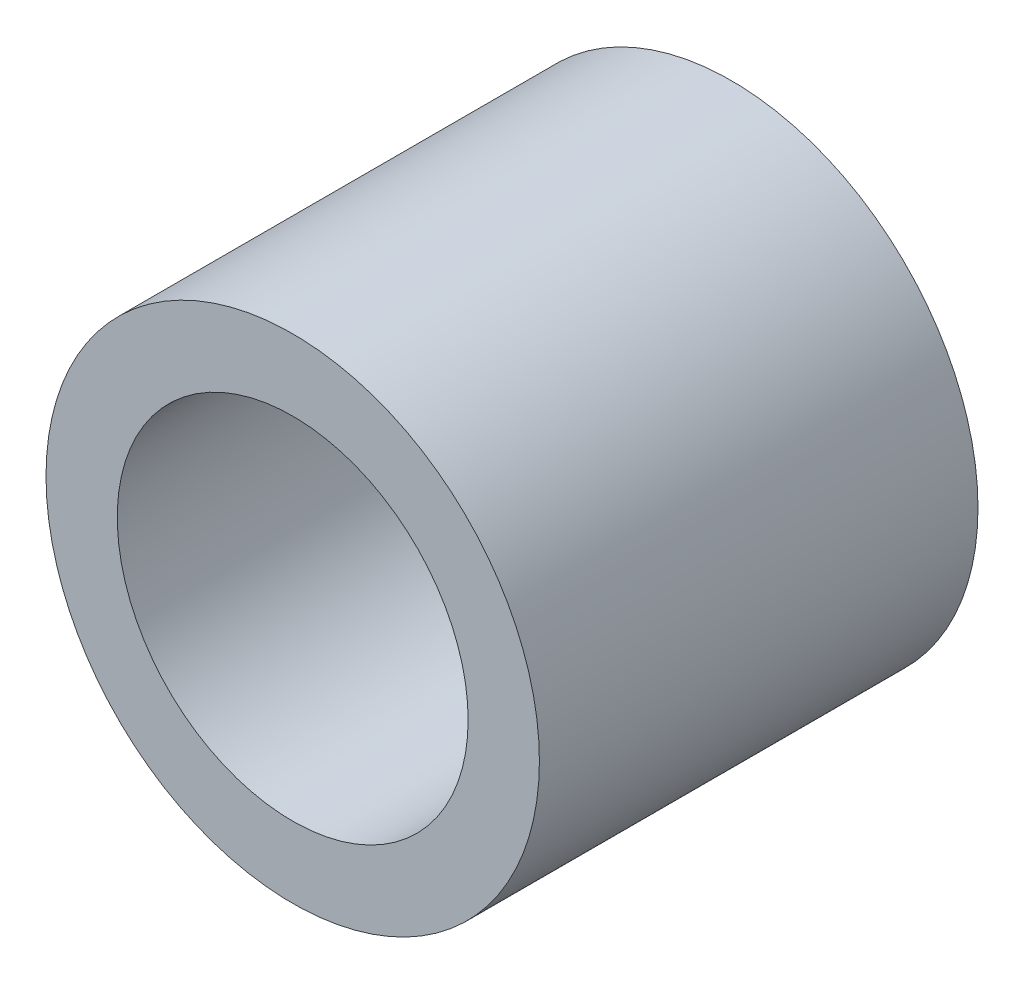
SolidWorks part; units mm, degrees
ref_plane "Front Plane" through (0, 0, 0) normal (0, 0, 1) x (1, 0, 0)
ref_plane "Top Plane" through (0, 0, 0) normal (0, 1, 0) x (1, 0, 0)
ref_plane "Right Plane" through (0, 0, 0) normal (1, 0, 0) x (0, 0, -1)
sketch "Sketch1" plane through (0, 0, 0) normal (0, 0, 1) x (1, 0, 0)
  circle A0 centre (0, 0) radius 2.25
  circle A1 centre (0, 0) radius 1.6
  dimension "D1" = 3.2
  dimension "D2" = 4.5
extrude "Boss-Extrude1" add sketch "Sketch1" along normal blind 4
